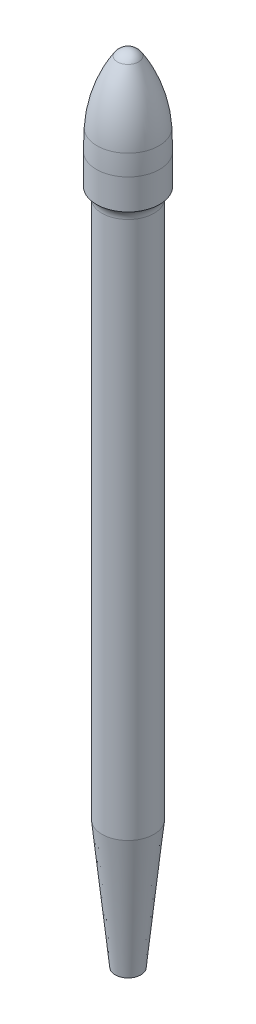
SolidWorks part; units mm, degrees
ref_plane "Frontal" through (0, 0, 0) normal (0, 0, 1) x (1, 0, 0)
ref_plane "Superior" through (0, 0, 0) normal (0, 1, 0) x (1, 0, 0)
ref_plane "Lateral" through (0, 0, 0) normal (1, 0, 0) x (0, 0, -1)
sketch "Esboço1" plane through (0, 0, 0) normal (0, 0, 1) x (1, 0, 0)
  line L0 (0, 0) -> (0, 31.9247) construction
  line L1 (-1.025, 5.08) -> (-0.51, 0)
  line L2 (-1.025, 5.08) -> (-1.025, 26.3824)
  line L3 (-0.51, 0) -> (0, 0)
  line L4 (-1.25, 26.8) -> (-1.25, 28)
  line L5 (0, 0) -> (0, 31.5)
  arc A0 (-1.025, 26.3824) -> (-1.25, 26.8) centre (-1.525, 26.3824) ccw
  arc A1 (-1.25, 28) -> (-1.2286, 28.8013) centre (13.75, 28) cw
  arc A2 (-0.4183, 31.274) -> (0, 31.5) centre (0, 31) cw
  arc A3 (-1.2286, 28.8013) -> (-0.4183, 31.274) centre (3.7643, 28.5342) cw
  point P13 (0, 31.5)
  dimension "D5" = 4.7
  dimension "D6" = 0.5
  dimension "D7" = 15
  dimension "D8" = 5
  dimension "D10" = 0.4176
  dimension "D11" = 0.5
  dimension "D1" = 1.02
  dimension "D2" = 5.08
  dimension "D3" = 2.05
  dimension "D4" = 2.5
  dimension "D9" = 3.5
  dimension "D12" = 31.5
revolve "Revolução1" add sketch "Esboço1" angle 360 about L0
